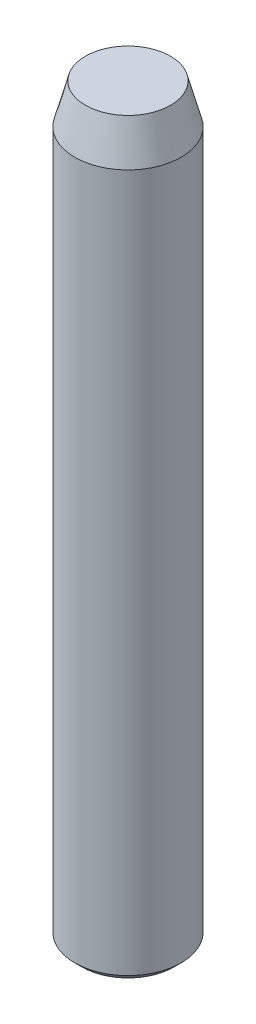
SolidWorks part; units mm, degrees
material "1.7131 (16MnCr5)"
ref_plane "Front Plane" through (0, 0, 0) normal (0, 0, 1) x (1, 0, 0)
ref_plane "Top Plane" through (0, 0, 0) normal (0, 1, 0) x (1, 0, 0)
ref_plane "Right Plane" through (0, 0, 0) normal (1, 0, 0) x (0, 0, -1)
sketch "Sketch1" plane through (0, 0, 0) normal (0, 1, 0) x (1, 0, 0)
  circle A0 centre (0, 0) radius 15
  dimension "D1" = 30
extrude "Boss-Extrude1" add sketch "Sketch1" against normal blind 210
chamfer "Chamfer1" distance 2 angle 45 1 edges at (0, -210, 15)
chamfer "Chamfer2" distance 3 angle 75 1 edges at (0, 0, 15)
